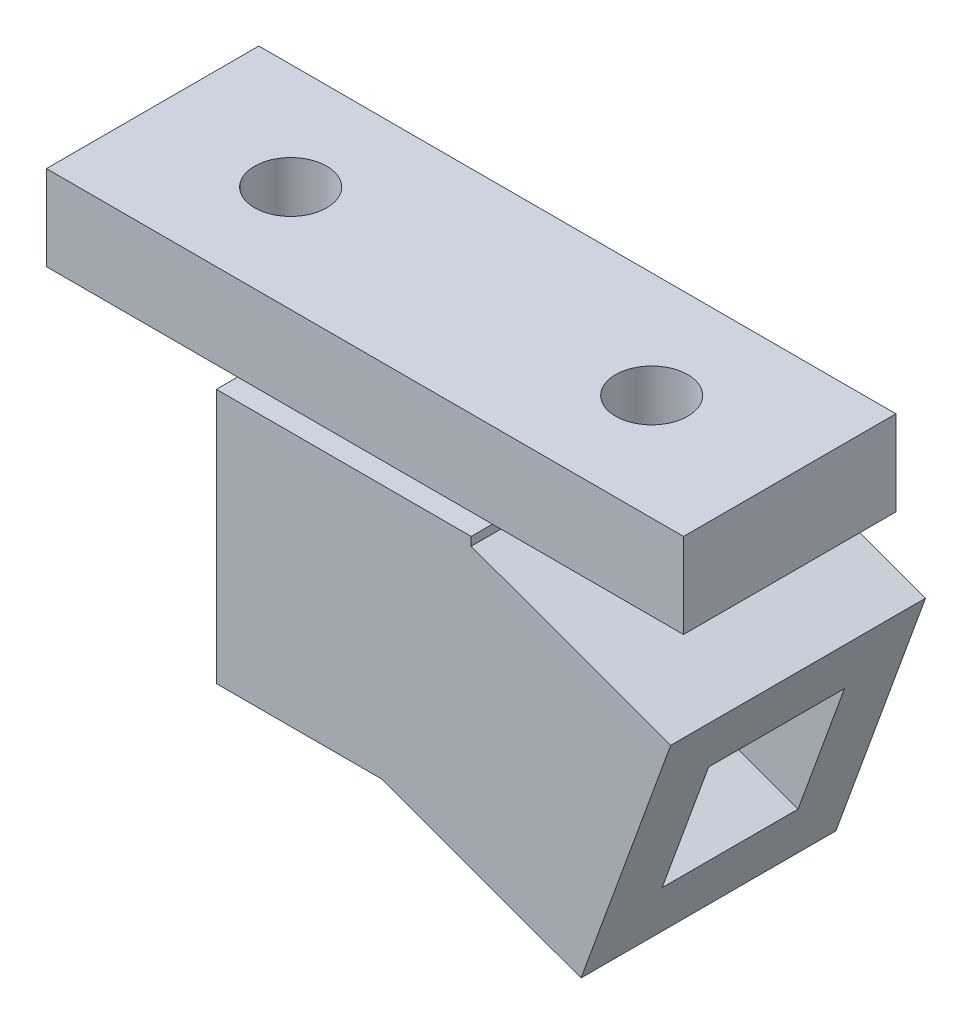
SolidWorks part; units mm, degrees
ref_plane "前视基准面" through (0, 0, 0) normal (0, 0, 1) x (1, 0, 0)
ref_plane "上视基准面" through (0, 0, 0) normal (0, 1, 0) x (1, 0, 0)
ref_plane "右视基准面" through (0, 0, 0) normal (1, 0, 0) x (0, 0, -1)
other "Configuration Table"
sketch "草图1" plane through (0, 0, 0) normal (0, 1, 0) x (1, 0, 0)
  line L0 (7.5, 5) -> (7.5, 0) construction
  line L1 (0, 0) -> (15, 0)
  line L2 (0, 0) -> (0, 5)
  line L3 (0, 5) -> (15, 5)
  line L4 (15, 0) -> (15, 5)
  circle A0 centre (3.25, 2.5) radius 0.85
  circle A1 centre (11.75, 2.5) radius 0.85
  point P12 (0, 2.5)
  dimension "D3" = 1.7
  dimension "D1" = 15
  dimension "D2" = 5
  dimension "D4" = 8.5
extrude "凸台-拉伸1" add sketch "草图1" along normal blind 2 contours L2 L1 L4 L3 | A0 | A1
sketch "草图2" plane through (0, 0, 0) normal (0, -1, 0) x (1, 0, 0)
  line L7 (0, 0) -> (15, 0) construction
  line L9 (0, -5) -> (15, -5) construction
  line L11 (7.5, 0) -> (7.5, -5) construction
  line L13 (10.5, 0.5) -> (4.5, 0.5)
  line L14 (4.5, 0.5) -> (4.5, -5.5)
  line L16 (10.5, 0.5) -> (10.5, -5.5)
  line L17 (0, -2.5) -> (15, -2.5) construction
  line L18 (0, 0) -> (0, -5) construction
  line L19 (15, 0) -> (15, -5) construction
  line L20 (10.5, -5.5) -> (4.5, -5.5)
  point P11 (7.5, 0.5)
  point P12 (7.5, -6.9299)
  dimension "D1" = 6
  dimension "D2" = 6
extrude "凸台-拉伸3" add sketch "草图2" along normal blind 6
sketch "草图6" plane through (0, 0, -5.5) normal (0, 0, -1) x (-1, 0, 0)
  line L0 (-10.5, -0.2) -> (-10.5, -6)
  line L1 (-10.5, -6) -> (-10.5, 0) construction
  line L2 (-10.5, -6) -> (-8.389, -6)
  line L3 (-4.5, -6) -> (-10.5, -6) construction
  line L4 (-8.389, -6) -> (-10.5, -0.2)
  dimension "D1" = 20
  dimension "D2" = 5.8
extrude "切除-拉伸2" cut sketch "草图6" against normal up to surface (6 mm away) up to face at (7.5, -3, 0.5)
sketch "草图7" plane through (9.336, -3.398, 0) normal (0.9397, -0.342, 0) x (0, 0, -1)
  line L0 (-0.5, 0.3172) -> (5.5, 0.3172) construction
  line L1 (-0.5, 3.4033) -> (-0.5, -2.769) construction
  line L2 (5.5, -2.769) -> (5.5, 3.4033) construction
  line L3 (4.1, 1.9172) -> (0.9, 1.9172)
  line L4 (-0.5, 3.4033) -> (5.5, 3.4033) construction
  line L5 (2.5, 3.4033) -> (2.5, -2.769) construction
  line L6 (-0.5, -2.769) -> (5.5, -2.769) construction
  line L7 (0.9, 1.9172) -> (0.9, -1.2828)
  line L8 (4.1, -1.2828) -> (0.9, -1.2828)
  line L9 (4.1, 1.9172) -> (4.1, -1.2828)
  point P16 (0.9, 0.3172)
  point P18 (2.5, -1.2828)
  point P19 (2.5, 1.9172)
  dimension "D1" = 3.2
  dimension "D2" = 3.2
extrude "切除-拉伸3" cut sketch "草图7" against normal blind 2
sketch "草图10" plane through (9.336, -3.398, 0) normal (0.9397, -0.342, 0) x (0, 0, -1)
  line L1 (0.9, 1.9172) -> (4.1, 1.9172)
  line L2 (0.9, 1.9172) -> (0.9, -1.2828)
  line L3 (0.9, -1.2828) -> (4.1, -1.2828)
  line L4 (4.1, 1.9172) -> (4.1, -1.2828)
  line L5 (-0.5, 3.4033) -> (5.5, 3.4033)
  line L6 (-0.5, 3.4033) -> (-0.5, -2.769)
  line L7 (-0.5, -2.769) -> (5.5, -2.769)
  line L8 (5.5, 3.4033) -> (5.5, -2.769)
extrude "凸台-拉伸4" add sketch "草图10" along normal blind 5
